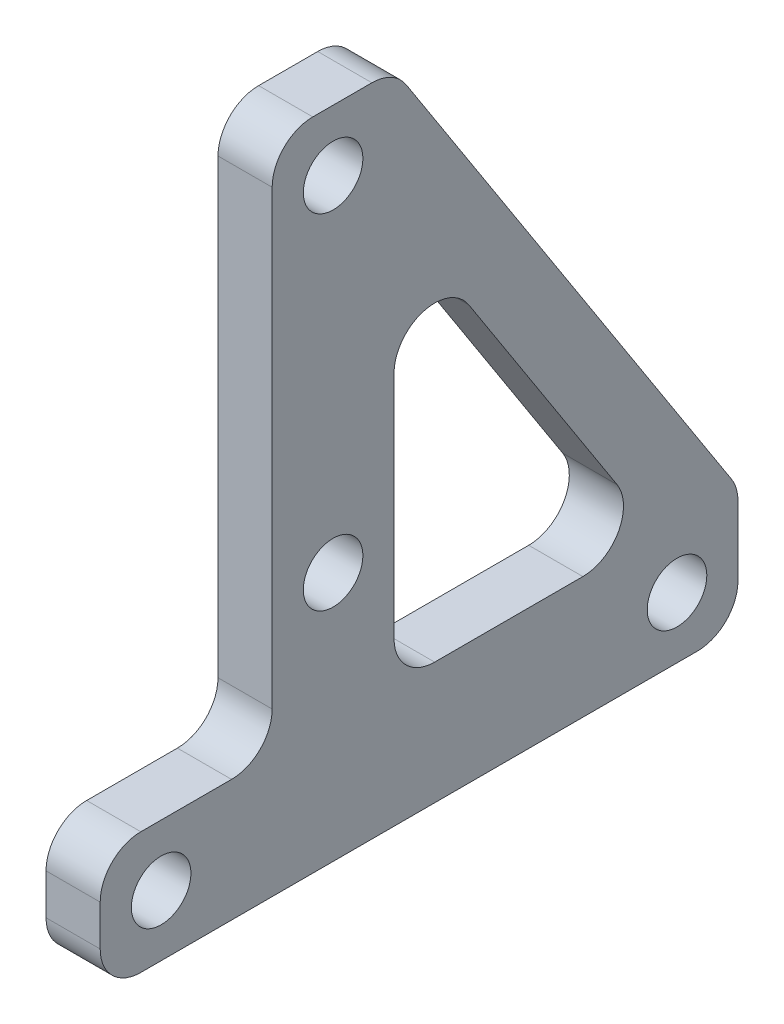
SolidWorks part; units mm, degrees
ref_plane "Front Plane" through (0, 0, 0) normal (0, 0, 1) x (1, 0, 0)
ref_plane "Top Plane" through (0, 0, 0) normal (0, 1, 0) x (1, 0, 0)
ref_plane "Right Plane" through (0, 0, 0) normal (1, 0, 0) x (0, 0, -1)
sketch "Sketch1" plane through (0, 0, 0) normal (1, 0, 0) x (0, 0, -1)
  line L0 (-4.5, 4.5) -> (-17.2, 4.5)
  line L1 (-17.2, 4.5) -> (-17.2, -4.5)
  line L2 (-17.2, -4.5) -> (29.9, -4.5)
  line L3 (29.9, -4.5) -> (29.9, 4.5)
  line L4 (29.9, 4.5) -> (4.5, 43.87)
  line L5 (4.5, 43.87) -> (-4.5, 43.87)
  line L6 (-4.5, 43.87) -> (-4.5, 4.5)
  line L7 (4.5, 4.5) -> (23.9497, 4.5)
  line L8 (23.9497, 4.5) -> (4.5, 34.6471)
  line L9 (4.5, 34.6471) -> (4.5, 4.5)
  circle A1 centre (25.4, 0) radius 2.2
  circle A2 centre (0, 13.97) radius 2.2
  circle A3 centre (0, 39.37) radius 2.2
  circle A4 centre (-12.7, 0) radius 2.2
  dimension "D1" = 4.4
  dimension "D2" = 12.7
  dimension "D3" = 25.4
  dimension "D4" = 13.97
  dimension "D5" = 25.4
  dimension "D6" = 4.5
  dimension "D7" = 4.5
  dimension "D8" = 4.5
  dimension "D9" = 9
  dimension "D10" = 4.5
  dimension "D11" = 4.5
  dimension "D12" = 9
  dimension "D13" = 9
  dimension "D14" = 5
extrude "Boss-Extrude1" add sketch "Sketch1" along normal blind 4
fillet "Fillet1" radius 3 10 edges at (2, 4.5, 4.5) (2, -4.5, 17.2) (2, 4.5, 17.2) (2, -4.5, -29.9) (2, 4.5, -29.9) (2, 43.87, -4.5) (2, 43.87, 4.5) (2, 4.5, -4.5) (2, 4.5, -23.9497) (2, 34.6471, -4.5)
sketch "Sketch2" plane through (0, 0, 0) normal (1, 0, 0) x (0, 0, -1)
  line L1 (2.3114, 2.3114) -> (-2.3114, 2.3114)
  line L2 (2.3114, 2.3114) -> (2.3114, -2.3114)
  line L3 (2.3114, -2.3114) -> (-2.3114, -2.3114)
  line L4 (-2.3114, 2.3114) -> (-2.3114, -2.3114)
  line L5 (2.3114, 2.3114) -> (-2.3114, -2.3114) construction
  line L6 (2.3114, -2.3114) -> (-2.3114, 2.3114) construction
  line L7 (15.0114, 2.3114) -> (10.3886, 2.3114)
  line L8 (15.0114, 2.3114) -> (15.0114, -2.3114)
  line L9 (15.0114, -2.3114) -> (10.3886, -2.3114)
  line L10 (10.3886, 2.3114) -> (10.3886, -2.3114)
  line L11 (15.0114, 2.3114) -> (10.3886, -2.3114) construction
  line L12 (15.0114, -2.3114) -> (10.3886, 2.3114) construction
  line L13 (-2.3114, 28.9814) -> (2.3114, 28.9814)
  line L14 (-2.3114, 28.9814) -> (-2.3114, 24.3586)
  line L15 (-2.3114, 24.3586) -> (2.3114, 24.3586)
  line L16 (2.3114, 28.9814) -> (2.3114, 24.3586)
  line L17 (-2.3114, 28.9814) -> (2.3114, 24.3586) construction
  line L18 (-2.3114, 24.3586) -> (2.3114, 28.9814) construction
  point P0 (0, 0)
  point P6 (12.7, 0)
  point P11 (0, 26.67)
  point P16 (0, 13.97)
  dimension "D1" = 12.7
  dimension "D2" = 12.7
  dimension "D3" = 4.6228
extrude "Boss-Extrude2" add sketch "Sketch2" against normal blind 2
fillet "Fillet2" radius 0.508 12 edges at (-1, 2.3114, -15.0114) (-1, 2.3114, -10.3886) (-1, -2.3114, -10.3886) (-1, -2.3114, -15.0114) (-1, -2.3114, -2.3114) (-1, 2.3114, -2.3114) (-1, 2.3114, 2.3114) (-1, -2.3114, 2.3114) (-1, 28.9814, 2.3114) (-1, 28.9814, -2.3114) (-1, 24.3586, -2.3114) (-1, 24.3586, 2.3114)
fillet "Fillet3" radius 0.508 24 edges at (-2, -2.1626, -10.5374) (-2, 0, -10.3886) (-2, 2.1626, -10.5374) (-2, 2.3114, -12.7) (-2, 2.1626, -14.8626) (-2, 0, -15.0114) (-2, -2.1626, -14.8626) (-2, -2.1626, 2.1626) (-2, 0, 2.3114) (-2, 2.1626, 2.1626) (-2, 2.3114, 0) (-2, 2.1626, -2.1626) (-2, 0, -2.3114) (-2, -2.1626, -2.1626) (-2, 24.5074, 2.1626) (-2, 26.67, 2.3114) (-2, 28.8326, 2.1626) (-2, 28.9814, 0) (-2, 28.8326, -2.1626) (-2, 26.67, -2.3114) (-2, 24.5074, -2.1626) (-2, -2.3114, -12.7) (-2, -2.3114, 0) (-2, 24.3586, 0)
